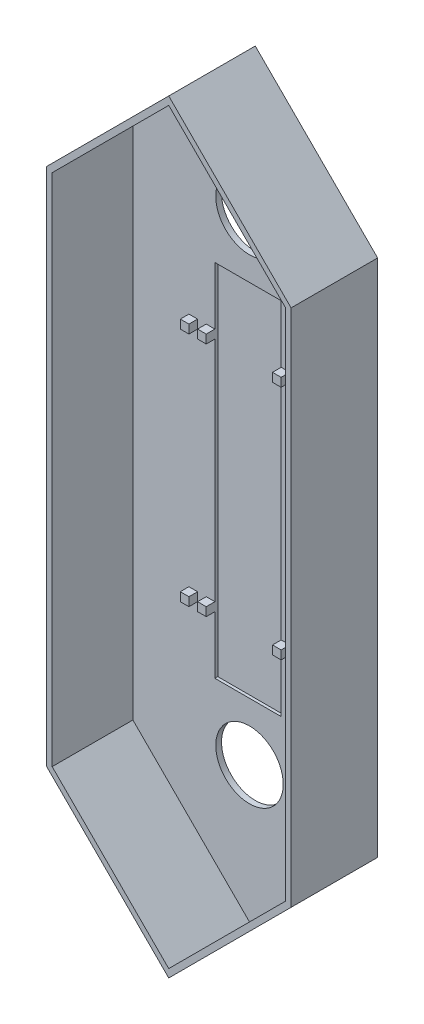
SolidWorks part; units mm, degrees
ref_plane "Спереди" through (0, 0, 0) normal (0, 0, 1) x (1, 0, 0)
ref_plane "Сверху" through (0, 0, 0) normal (0, 1, 0) x (1, 0, 0)
ref_plane "Справа" through (0, 0, 0) normal (1, 0, 0) x (0, 0, -1)
sketch "Эскиз1" plane through (0, 0, 0) normal (0, 0, 1) x (1, 0, 0)
  line L0 (0, 82.8541) -> (0, -105.2575) construction
  line L1 (-108.5711, 0) -> (115.0769, 0) construction
  line L2 (-21.2132, -45) -> (-21.2132, 45)
  line L3 (-21.2132, 45) -> (0, 66.2132)
  line L4 (0, 66.2132) -> (21.2132, 45)
  line L5 (21.2132, 45) -> (21.2132, -45)
  line L6 (21.2132, -45) -> (0, -66.2132)
  line L7 (0, -66.2132) -> (-21.2132, -45)
  line L8 (10.6066, 55.6066) -> (9.172, 57.0412) construction
  line L9 (-21.2132, 45) -> (21.2132, 45) construction
  line L10 (-21.2132, -45) -> (21.2132, -45) construction
  line L11 (21.2132, -45) -> (21.1275, -44.9594) construction
  point P7 (-21.2132, 0)
  dimension "D1" = 90
  dimension "D2" = 30
  dimension "D3" = 90
extrude "Вытянуть-Тонкостенный3" add sketch "Эскиз1" along normal blind 15 thin
sketch "Эскиз2" plane through (0, 0, 0) normal (0, 0, -1) x (-1, 0, 0)
  line L1 (-20.2132, -44.5858) -> (0, -64.799)
  line L2 (0, -64.799) -> (20.2132, -44.5858)
  line L3 (20.2132, -44.5858) -> (20.2132, 44.5858)
  line L4 (20.2132, 44.5858) -> (20.2132, -44.5858) construction
  line L5 (0, 64.799) -> (20.2132, 44.5858) construction
  line L6 (20.2132, 44.5858) -> (0, 64.799)
  line L7 (0, 64.799) -> (-20.2132, 44.5858)
  line L8 (-20.2132, 44.5858) -> (-20.2132, -44.5858)
extrude "Бобышка-Вытянуть2" add sketch "Эскиз2" against normal blind 1
sketch "Эскиз4" plane through (0, 0, 1) normal (0, 0, 1) x (1, 0, 0)
  line L0 (0, 64.799) -> (0, -64.799) construction
  line L2 (-20.2132, 44.5858) -> (18.9225, 44.5858) construction
  line L3 (-20.2132, -44.5858) -> (20.2132, -44.5858) construction
  circle A0 centre (0, 41.2158) radius 5.85
  circle A1 centre (0, -41.2158) radius 5.85
  dimension "D1" = 11.7
  dimension "D2" = 3.37
  dimension "D3" = 3.37
extrude "Вырез-Вытянуть1" cut sketch "Эскиз4" against normal blind 2
sketch "Skizze1" plane through (0, 0, 1) normal (0, 0, 1) x (1, 0, 0)
  line L0 (0, 64.799) -> (0, -59.88) construction
  line L1 (-6, 31.2158) -> (5.4871, 31.2158)
  line L2 (-6, 31.2158) -> (-6, -31.2158)
  line L3 (-6, -31.2158) -> (5.4871, -31.2158)
  line L4 (5.4871, 31.2158) -> (5.4871, -31.2158)
  circle A0 centre (0, 41.2158) radius 5.85 construction
  circle A1 centre (0, -41.2158) radius 5.85 construction
  dimension "D1" = 11.4871
  dimension "D2" = 6
  dimension "D3" = 10
  dimension "D4" = 10
extrude "Schnitt-Linear austragen1" cut sketch "Skizze1" against normal blind 0.5
sketch "Skizze2" plane through (0, 0, 1) normal (0, 0, 1) x (1, 0, 0)
  line L0 (5.4871, -31.2158) -> (5.4871, 31.2158) construction
  line L1 (5.4871, 21.2158) -> (6.9871, 21.2158)
  line L2 (5.4871, 21.2158) -> (5.4871, 19.7158)
  line L3 (5.4871, 19.7158) -> (6.9871, 19.7158)
  line L4 (6.9871, 21.2158) -> (6.9871, 19.7158)
  line L5 (5.4871, 31.2158) -> (-6, 31.2158) construction
  line L6 (8.4871, 21.2158) -> (9.9871, 21.2158)
  line L7 (8.4871, 21.2158) -> (8.4871, 19.7158)
  line L8 (8.4871, 19.7158) -> (9.9871, 19.7158)
  line L9 (9.9871, 21.2158) -> (9.9871, 19.7158)
  line L10 (-6, 31.2158) -> (-6, -31.2158) construction
  line L11 (-6, 21.2158) -> (-7.5, 21.2158)
  line L12 (-6, 21.2158) -> (-6, 19.7158)
  line L13 (-6, 19.7158) -> (-7.5, 19.7158)
  line L14 (-7.5, 21.2158) -> (-7.5, 19.7158)
  line L15 (5.4871, -31.2158) -> (5.4871, 31.2158) construction
  line L16 (-9, 21.2158) -> (-10.5, 21.2158)
  line L17 (-9, 21.2158) -> (-9, 19.7158)
  line L18 (-9, 19.7158) -> (-10.5, 19.7158)
  line L19 (-10.5, 21.2158) -> (-10.5, 19.7158)
  line L20 (5.4871, -19.7158) -> (6.9871, -19.7158)
  line L21 (5.4871, -19.7158) -> (5.4871, -21.2158)
  line L22 (5.4871, -21.2158) -> (6.9871, -21.2158)
  line L23 (6.9871, -19.7158) -> (6.9871, -21.2158)
  line L24 (-6, 31.2158) -> (-6, -31.2158) construction
  line L25 (8.4871, -19.7158) -> (9.9871, -19.7158)
  line L26 (8.4871, -19.7158) -> (8.4871, -21.2158)
  line L27 (8.4871, -21.2158) -> (9.9871, -21.2158)
  line L28 (9.9871, -19.7158) -> (9.9871, -21.2158)
  line L29 (-6, -19.7158) -> (-7.5, -19.7158)
  line L30 (-6, -19.7158) -> (-6, -21.2158)
  line L31 (-6, -21.2158) -> (-7.5, -21.2158)
  line L32 (-7.5, -19.7158) -> (-7.5, -21.2158)
  line L33 (5.4871, 31.2158) -> (-6, 31.2158) construction
  line L34 (-9, -19.7158) -> (-10.5, -19.7158)
  line L35 (-9, -19.7158) -> (-9, -21.2158)
  line L36 (-9, -21.2158) -> (-10.5, -21.2158)
  line L37 (-10.5, -19.7158) -> (-10.5, -21.2158)
  line L38 (-6, -31.2158) -> (5.4871, -31.2158) construction
  line L39 (-6, -31.2158) -> (5.4871, -31.2158) construction
  dimension "D1" = 1.5
  dimension "D2" = 1.5
  dimension "D3" = 10
  dimension "D4" = 1.5
  dimension "D5" = 1.5
  dimension "D6" = 10
  dimension "D7" = 1.5
  dimension "D8" = 1.5
  dimension "D9" = 10
  dimension "D10" = 1.5
  dimension "D11" = 1.5
  dimension "D12" = 10
extrude "Aufsatz-Linear austragen1" add sketch "Skizze2" along normal blind 1.5
